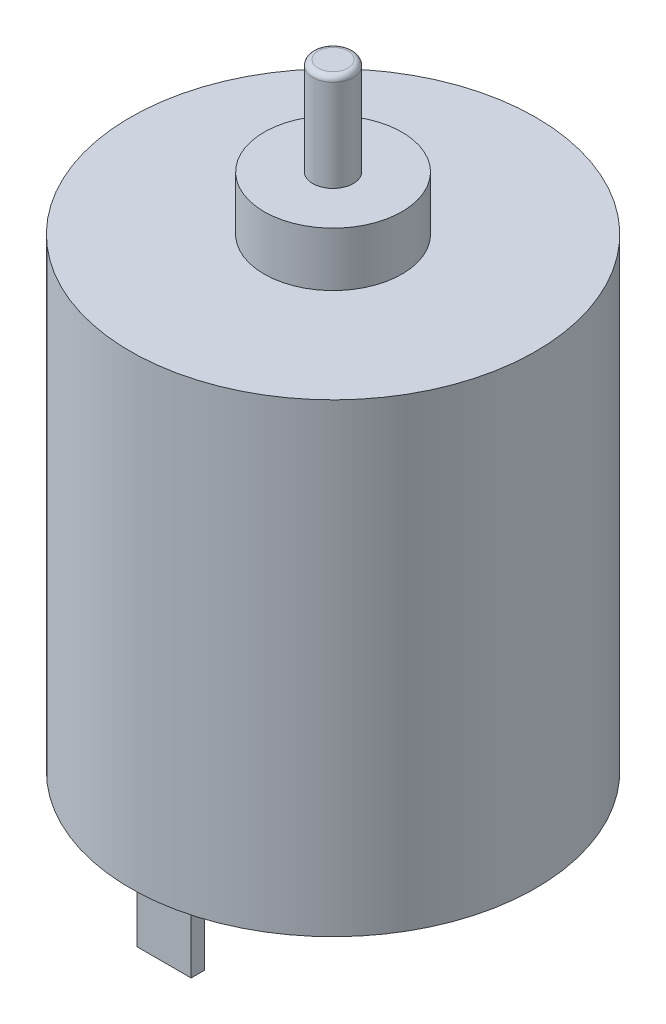
SolidWorks part; units mm, degrees
ref_plane "前基準面" through (0, 0, 0) normal (0, 0, 1) x (1, 0, 0)
ref_plane "上基準面" through (0, 0, 0) normal (0, 1, 0) x (1, 0, 0)
ref_plane "右基準面" through (0, 0, 0) normal (1, 0, 0) x (0, 0, -1)
sketch "草圖1" plane through (0, 0, 0) normal (0, 1, 0) x (1, 0, 0)
  circle A0 centre (0, 0) radius 7.5
  dimension "D1" = 15
extrude "伸長1" add sketch "草圖1" along normal blind 17.2
sketch "草圖2" plane through (0, 17.2, 0) normal (0, 1, 0) x (1, 0, 0)
  circle A0 centre (0, 0) radius 2.55
  dimension "D1" = 5.1
extrude "伸長2" add sketch "草圖2" along normal blind 2
sketch "草圖3" plane through (0, 19.2, 0) normal (0, 1, 0) x (-1, 0, 0)
  circle A0 centre (0, 0) radius 0.75
  dimension "D1" = 1.5
extrude "伸長3" add sketch "草圖3" along normal blind 3.6
sketch "草圖4" plane through (0, 0, 0) normal (0, -1, 0) x (1, 0, 0)
  line L0 (-7.5, 0) -> (7.5, 0) construction
  line L1 (0, 6.25) -> (0, -6.25) construction
  line L3 (-1, 5.75) -> (1, 5.75)
  line L4 (-1, 5.75) -> (-1, 6.25)
  line L5 (-1, 6.25) -> (1, 6.25)
  line L6 (1, 5.75) -> (1, 6.25)
  line L7 (-1, 5.75) -> (1, 6.25) construction
  line L8 (-1, 6.25) -> (1, 5.75) construction
  line L9 (-1, -5.75) -> (1, -5.75)
  line L10 (-1, -5.75) -> (-1, -6.25)
  line L11 (-1, -6.25) -> (1, -6.25)
  line L12 (1, -5.75) -> (1, -6.25)
  line L13 (-1, -5.75) -> (1, -6.25) construction
  line L14 (-1, -6.25) -> (1, -5.75) construction
  circle A0 centre (0, 0) radius 7.5 construction
  point P8 (0, 6)
  point P13 (0, -6)
  dimension "D1" = 12.5
  dimension "D2" = 0.5
  dimension "D3" = 2
extrude "伸長4" add sketch "草圖4" along normal blind 3
fillet "圓角2" radius 0.2 1 edges at (0, 22.8, 0.75)
